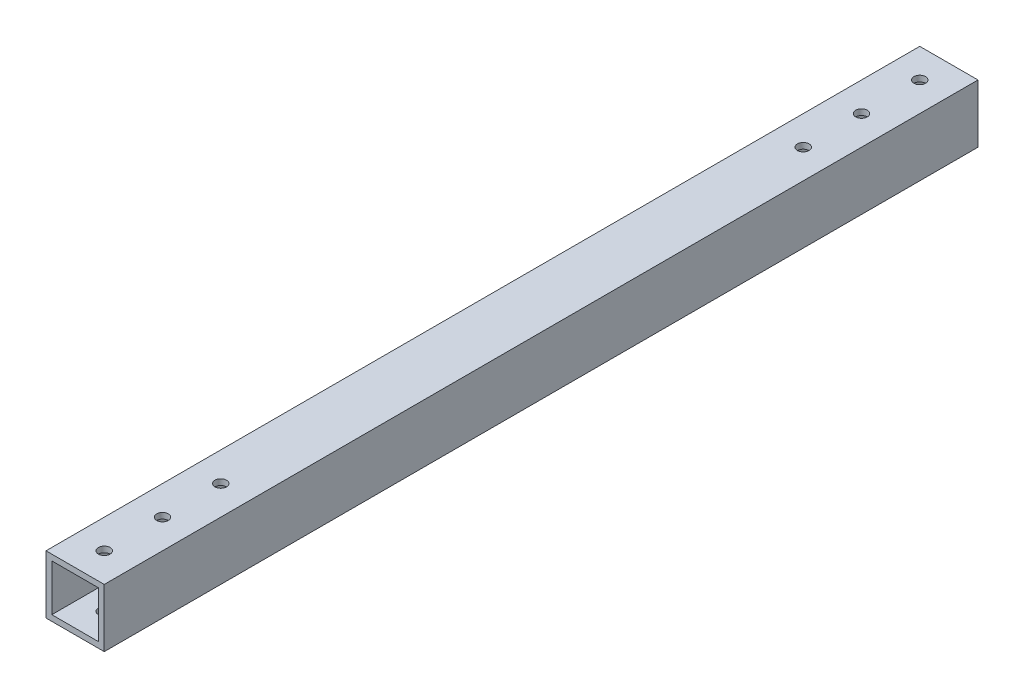
SolidWorks part; units mm, degrees
material "6061 合金"
ref_plane "前视基准面" through (0, 0, 0) normal (0, 0, 1) x (1, 0, 0)
ref_plane "上视基准面" through (0, 0, 0) normal (0, 1, 0) x (1, 0, 0)
ref_plane "右视基准面" through (0, 0, 0) normal (1, 0, 0) x (0, 0, -1)
other "Configuration Table"
sketch "草图1" plane through (0, 0, 0) normal (0, 0, 1) x (1, 0, 0)
  line L1 (0, 0) -> (20, 0)
  line L2 (0, 0) -> (0, 20)
  line L3 (0, 20) -> (20, 20)
  line L4 (20, 0) -> (20, 20)
  dimension "D1" = 20
  dimension "D2" = 20
extrude "拉伸-薄壁1" add sketch "草图1" along normal blind 300 thin thin type one direction reverse wall 2
sketch "草图2" plane through (0, 20, 0) normal (0, 1, 0) x (1, 0, 0)
  line L0 (10, -300) -> (10, -217.5608) construction
  line L1 (20, -300) -> (0, -300) construction
  line L2 (0, -150) -> (20, -150) construction
  line L3 (0, -300) -> (0, 0) construction
  line L4 (20, -300) -> (20, 0) construction
  circle A0 centre (10, -290) radius 2
  circle A1 centre (10, -270) radius 2
  circle A2 centre (10, -250) radius 2
  circle A3 centre (10, -10) radius 2
  circle A4 centre (10, -30) radius 2
  circle A5 centre (10, -50) radius 2
  dimension "D1" = 4
  dimension "D2" = 10
  dimension "D3" = 20
  dimension "D4" = 20
extrude "切除-拉伸1" cut sketch "草图2" against normal through all
sketch "草图3" plane through (0, 20, 0) normal (0, 1, 0) x (1, 0, 0)
  line L0 (0, -150) -> (20, -150) construction
  line L1 (0, -300) -> (0, 0) construction
  line L2 (20, -300) -> (20, 0) construction
  line L4 (0, -90) -> (20, -90)
  line L5 (0, -90) -> (0, -210)
  line L6 (0, -210) -> (20, -210)
  line L7 (20, -90) -> (20, -210)
  dimension "D1" = 120
extrude "切除-拉伸2" [suppressed] cut sketch "草图3" against normal through all
